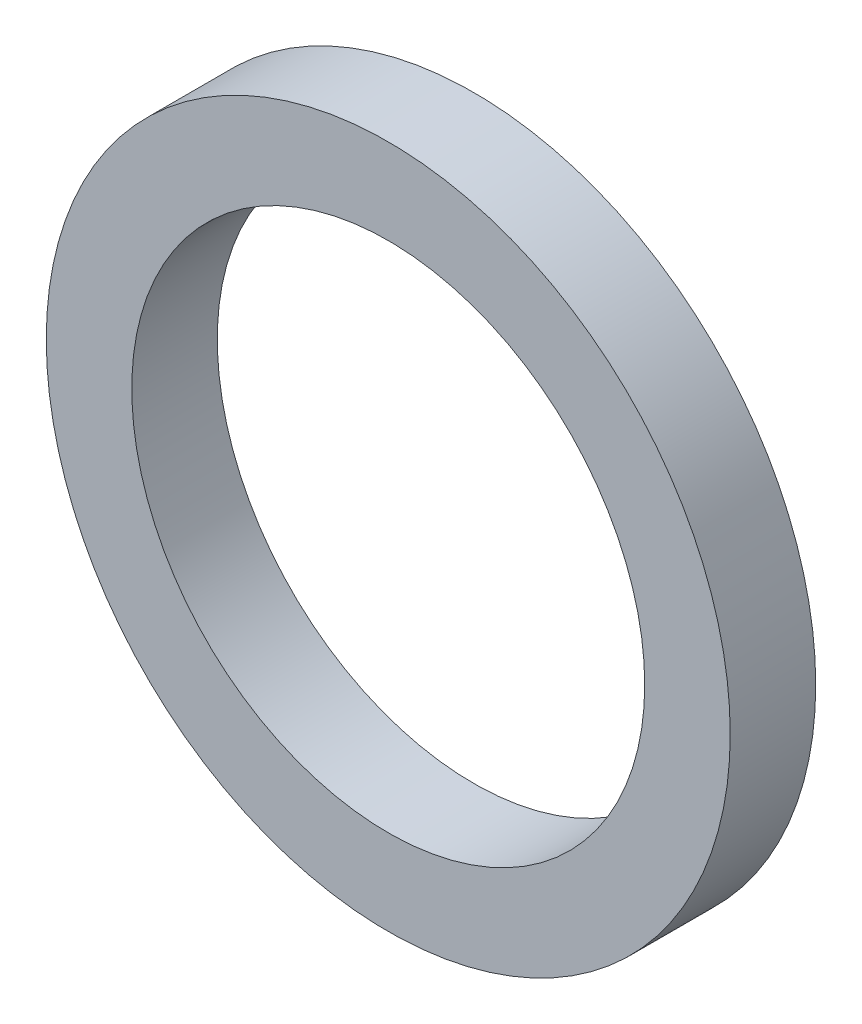
SolidWorks part; units mm, degrees
ref_plane "Front Plane" through (0, 0, 0) normal (0, 0, 1) x (1, 0, 0)
ref_plane "Top Plane" through (0, 0, 0) normal (0, 1, 0) x (1, 0, 0)
ref_plane "Right Plane" through (0, 0, 0) normal (1, 0, 0) x (0, 0, -1)
sketch "Sketch1" plane through (0, 0, 0) normal (0, 0, 1) x (1, 0, 0)
  circle A0 centre (0, 0) radius 38.1
  circle A1 centre (0, 0) radius 50.8
  dimension "D1" = 76.2
  dimension "D2" = 101.6
extrude "Boss-Extrude1" add sketch "Sketch1" along normal mid plane 12.7
